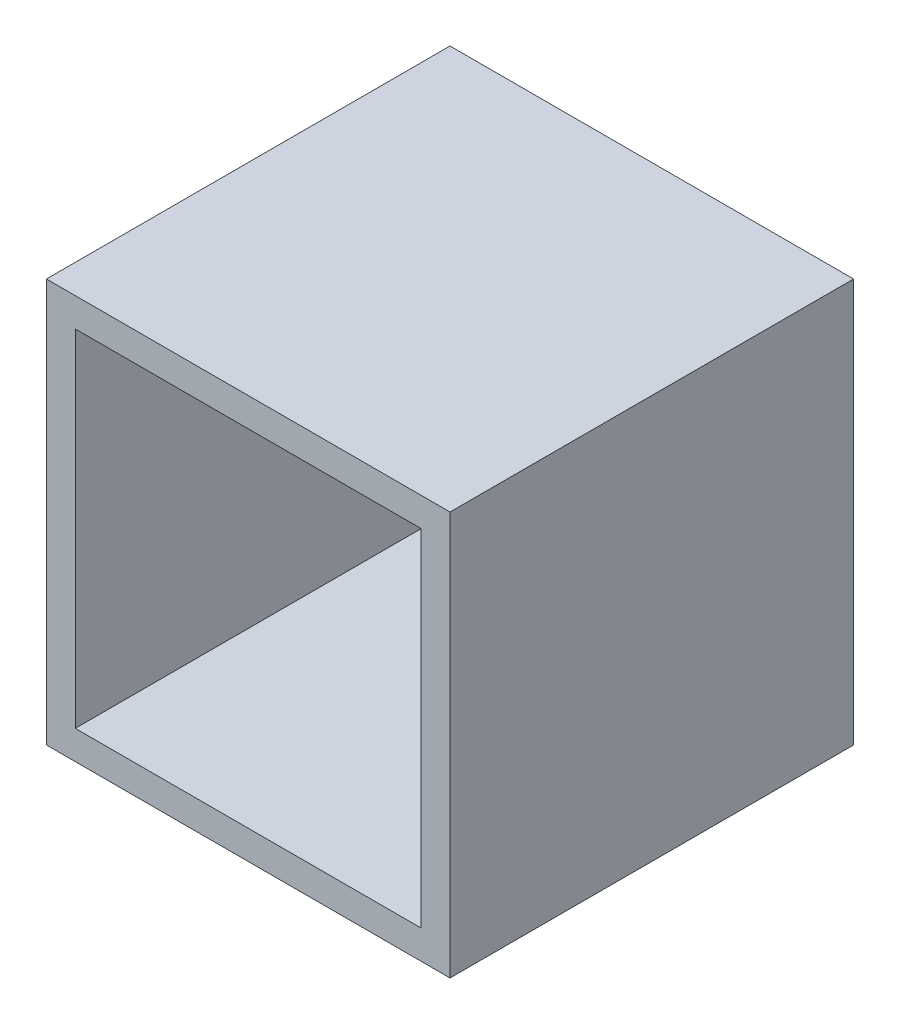
SolidWorks part; units mm, degrees
ref_plane "Front Plane" through (0, 0, 0) normal (0, 0, 1) x (1, 0, 0)
ref_plane "Top Plane" through (0, 0, 0) normal (0, 1, 0) x (1, 0, 0)
ref_plane "Right Plane" through (0, 0, 0) normal (1, 0, 0) x (0, 0, -1)
sketch "Sketch4" plane through (0, 0, 0) normal (0, 0, 1) x (1, 0, 0)
  line L1 (-20.2849, 20.5607) -> (14.7151, 20.5607)
  line L2 (-20.2849, 20.5607) -> (-20.2849, -14.4393)
  line L3 (-20.2849, -14.4393) -> (14.7151, -14.4393)
  line L4 (14.7151, 20.5607) -> (14.7151, -14.4393)
  dimension "D1" = 35
  dimension "D2" = 35
extrude "Boss-Extrude2" add sketch "Sketch4" along normal blind 35
sketch "Sketch5" plane through (0, 0, 35) normal (0, 0, 1) x (1, 0, 0)
  line L0 (-17.7849, -11.9393) -> (-17.7849, 18.0607)
  line L1 (-20.2849, -14.4393) -> (14.7151, -14.4393)
  line L2 (-20.2849, -14.4393) -> (-20.2849, 20.5607)
  line L3 (-20.2849, 20.5607) -> (14.7151, 20.5607)
  line L4 (14.7151, -14.4393) -> (14.7151, 20.5607)
  line L5 (-17.7849, 18.0607) -> (12.2151, 18.0607)
  line L6 (12.2151, -11.9393) -> (12.2151, 18.0607)
  line L7 (-17.7849, -11.9393) -> (12.2151, -11.9393)
  dimension "D1" = 2.5
extrude "Cut-Extrude2" cut sketch "Sketch5" against normal blind 32.5 flip side to cut
